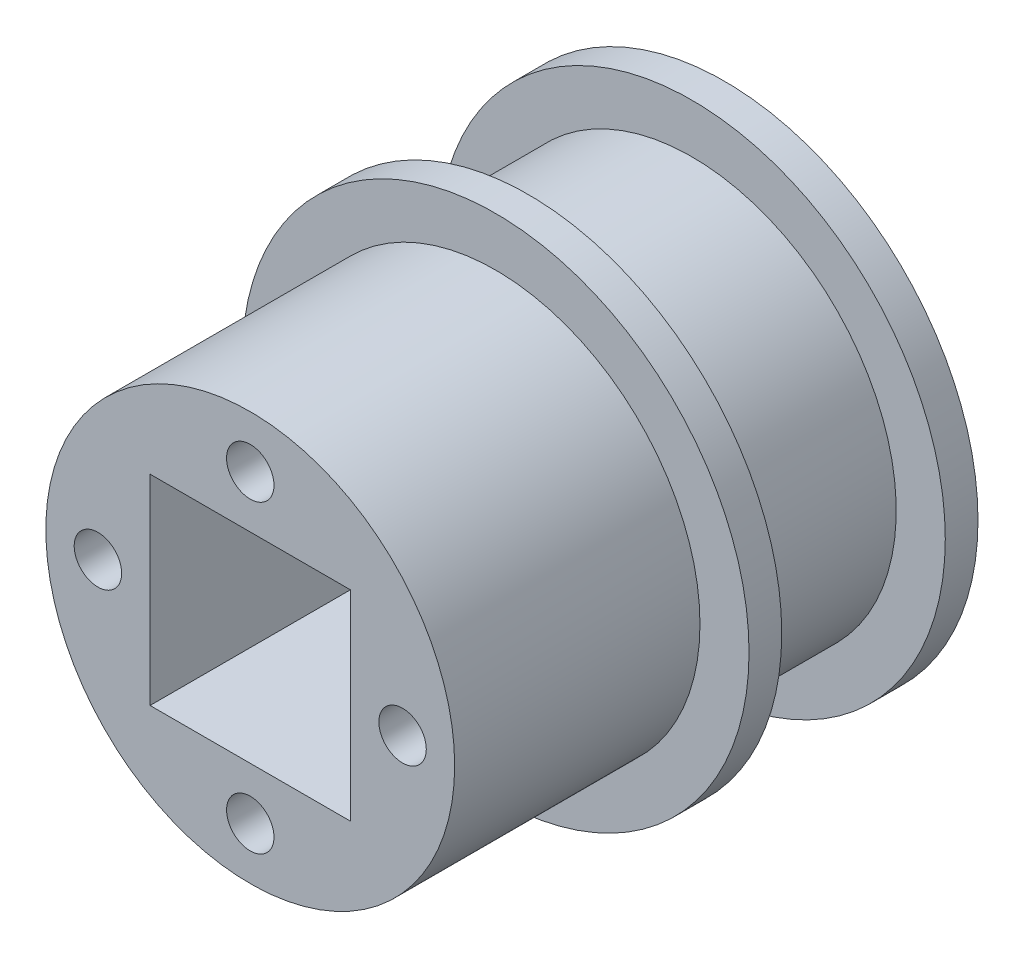
SolidWorks part; units mm, degrees
ref_plane "Front Plane" through (0, 0, 0) normal (0, 0, 1) x (1, 0, 0)
ref_plane "Top Plane" through (0, 0, 0) normal (0, 1, 0) x (1, 0, 0)
ref_plane "Right Plane" through (0, 0, 0) normal (1, 0, 0) x (0, 0, -1)
sketch "Sketch1" plane through (0, 0, 0) normal (0, 0, 1) x (1, 0, 0)
  circle A0 centre (0, 0) radius 12.5
  dimension "D2" = 25
extrude "Boss-Extrude1" add sketch "Sketch1" along normal mid plane 15
sketch "Sketch10" plane through (0, 0, 7.5) normal (0, 0, 1) x (1, 0, 0)
  circle A0 centre (0, 0) radius 12.5
  dimension "D1" = 25
sketch "Sketch13" plane through (0, 0, -7.5) normal (0, 0, -1) x (-1, 0, 0)
  circle A0 centre (0, 0) radius 15.5
  circle A1 centre (0, 0) radius 12.5 construction
  dimension "D1" = 3
extrude "Boss-Extrude2" add sketch "Sketch13" along normal blind 2
sketch "Sketch14" plane through (0, 0, -9.5) normal (0, 0, -1) x (-1, 0, 0)
  circle A0 centre (0, 0) radius 12.5
  circle A1 centre (0, 0) radius 12.5 construction
extrude "Boss-Extrude3" add sketch "Sketch14" along normal blind 10
sketch "Sketch15" plane through (0, 0, -19.5) normal (0, 0, -1) x (-1, 0, 0)
  circle A0 centre (0, 0) radius 15.5
  circle A1 centre (0, 0) radius 15.5 construction
extrude "Boss-Extrude4" add sketch "Sketch15" along normal blind 2
sketch "Sketch8" plane through (0, 0, 7.5) normal (0, 0, 1) x (1, 0, 0)
  line L2 (-6.125, 6.125) -> (6.125, 6.125)
  line L3 (-6.125, 6.125) -> (-6.125, -6.125)
  line L4 (-6.125, -6.125) -> (6.125, -6.125)
  line L5 (6.125, 6.125) -> (6.125, -6.125)
  line L6 (-6.125, 6.125) -> (6.125, -6.125) construction
  line L7 (-6.125, -6.125) -> (6.125, 6.125) construction
  point P5 (0, 0)
  point P14 (0, 0)
  dimension "D1" = 12.25
extrude "Cut-Extrude1" cut sketch "Sketch8" against normal up to next
sketch "Sketch11" plane through (0, 0, 7.5) normal (0, 0, 1) x (1, 0, 0)
  line L0 (6.125, -6.125) -> (6.125, 6.125) construction
  circle A0 centre (9.315, 0) radius 1.45
  circle A1 centre (0, -9.315) radius 1.45
  circle A2 centre (-9.315, 0) radius 1.45
  circle A3 centre (0, 9.315) radius 1.45
  point P13 (0, 0)
  dimension "D1" = 2.9
  dimension "D2" = 3.19
  dimension "D3" = 4
extrude "Cut-Extrude4" cut sketch "Sketch11" against normal up to next
equation "\"drumDiameter\"= 25"
equation "\"D2@Sketch1\"= \"drumDiameter\""
equation "\"drumLength\"=15"
equation "\"foamThickness\"= 5"
equation "\"drumAbove\"= 0.6"
equation "\"holderThicc\"= 2"
equation "\"D1@Boss-Extrude1\"=\"drumLength\""
equation "\"squareBarLength\"= 12.25"
equation "\"D1@Sketch8\"=\"squareBarLength\""
equation "\"D1@Sketch10\"=\"drumDiameter\""
equation "\"toothlen\"= 2.5"
